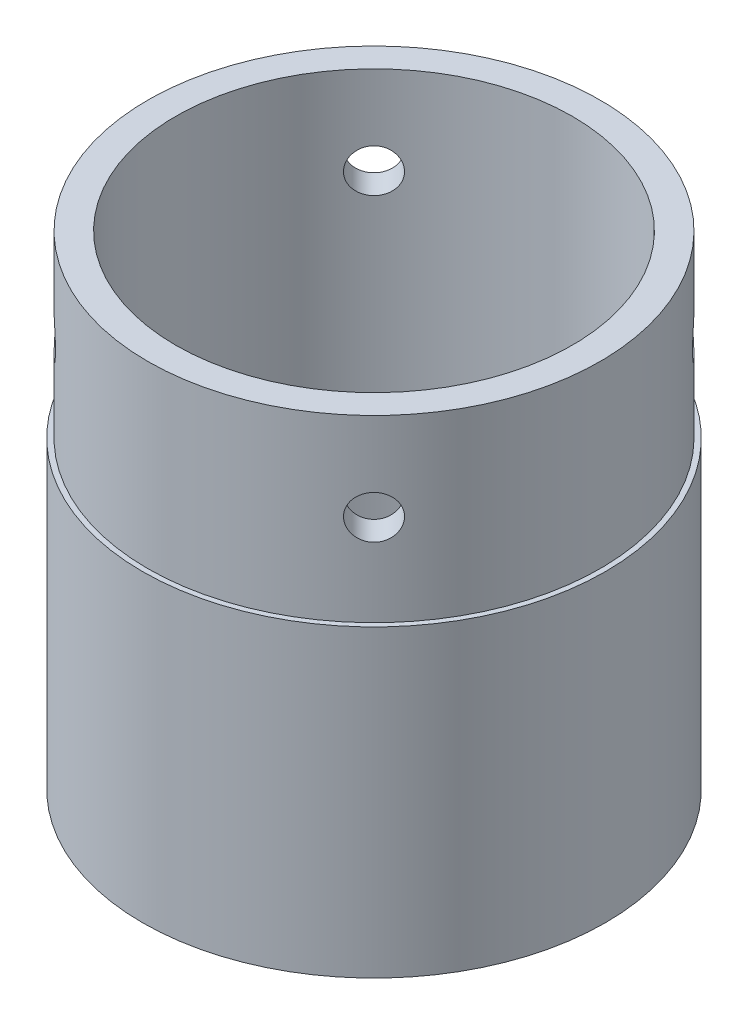
SolidWorks part; units mm, degrees
ref_plane "Front Plane" through (0, 0, 0) normal (0, 0, 1) x (1, 0, 0)
ref_plane "Top Plane" through (0, 0, 0) normal (0, 1, 0) x (1, 0, 0)
ref_plane "Right Plane" through (0, 0, 0) normal (1, 0, 0) x (0, 0, -1)
sketch "Sketch1" plane through (0, 0, 0) normal (0, 1, 0) x (1, 0, 0)
  circle A0 centre (0, 0) radius 32.6
  circle A1 centre (0, 0) radius 37.2
  dimension "D1" = 74.4
  dimension "D2" = 65.2
extrude "Boss-Extrude1" add sketch "Sketch1" along normal blind 29.5
ref_plane "Plane1" through (-26.3044, 0, -26.3044) normal (-0.7071, 0, -0.7071) x (0, -1, 0)
sketch "Sketch2" plane through (-26.3044, 0, -26.3044) normal (-0.7071, 0, -0.7071) x (0, -1, 0)
  circle A0 centre (-15, 0) radius 3.55
  dimension "D1" = 15
  dimension "D2" = 7.1
extrude "Cut-Extrude1" cut sketch "Sketch2" against normal up to next
pattern_circular "CirPattern1" count 4 over 360 about axis through (0, 29.5, 0) along (0, -1, 0) of "Cut-Extrude1"
sketch "Sketch3" plane through (0, 0, 0) normal (0, -1, 0) x (1, 0, 0)
  circle A0 centre (0, 0) radius 38.05
  circle A1 centre (0, 0) radius 32.6
  dimension "D1" = 76.1
extrude "Boss-Extrude2" add sketch "Sketch3" along normal blind 50
